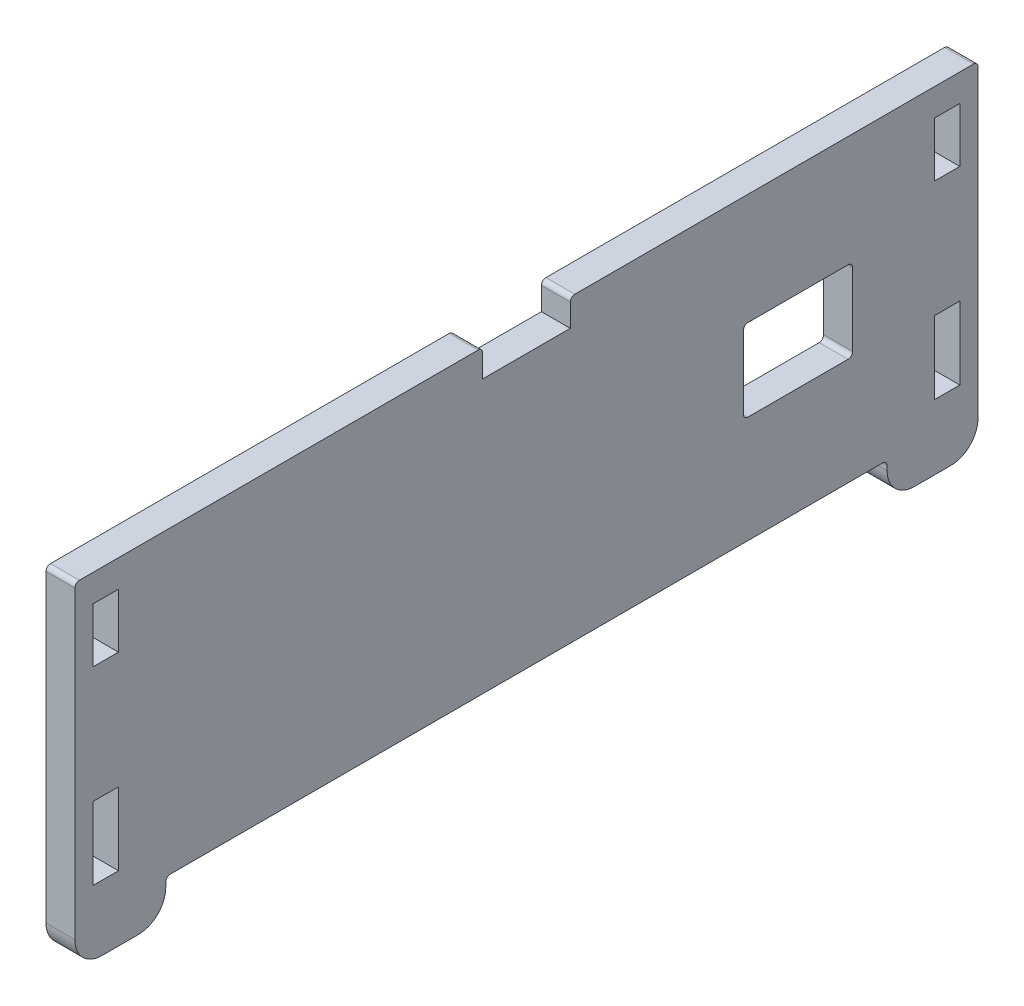
SolidWorks part; units mm, degrees
ref_plane "Front Plane" through (0, 0, 0) normal (0, 0, 1) x (1, 0, 0)
ref_plane "Top Plane" through (0, 0, 0) normal (0, 1, 0) x (1, 0, 0)
ref_plane "Right Plane" through (0, 0, 0) normal (1, 0, 0) x (0, 0, -1)
sketch "Sketch1" plane through (0, 0, 0) normal (1, 0, 0) x (0, 0, -1)
  line L1 (-49.675, -18.5) -> (49.675, -18.5)
  line L2 (-49.675, -18.5) -> (-49.675, 18.5)
  line L3 (-49.675, 18.5) -> (49.675, 18.5)
  line L4 (49.675, -18.5) -> (49.675, 18.5)
  line L5 (-49.675, -18.5) -> (49.675, 18.5) construction
  line L6 (-49.675, 18.5) -> (49.675, -18.5) construction
  point P0 (0, 0)
  dimension "D1" = 99.35
  dimension "D2" = 37
extrude "Boss-Extrude1" add sketch "Sketch1" along normal blind 3.175
sketch "Sketch2" plane through (3.175, 0, 0) normal (1, 0, 0) x (0, 0, -1)
  line L0 (49.675, 18.5) -> (-49.675, 18.5) construction
  line L1 (-47.675, 15.5) -> (-44.875, 15.5)
  line L2 (-47.675, 15.5) -> (-47.675, 9.5)
  line L3 (-47.675, 9.5) -> (-44.875, 9.5)
  line L4 (-44.875, 15.5) -> (-44.875, 9.5)
  line L5 (-49.675, 18.5) -> (-49.675, -18.5) construction
  line L6 (49.675, -18.5) -> (49.675, 18.5) construction
  line L7 (44.875, 15.5) -> (47.675, 15.5)
  line L8 (44.875, 15.5) -> (44.875, 9.5)
  line L9 (44.875, 9.5) -> (47.675, 9.5)
  line L10 (47.675, 15.5) -> (47.675, 9.5)
  line L11 (-49.675, -18.5) -> (49.675, -18.5) construction
  line L12 (-47.675, -3.325) -> (-44.875, -3.325)
  line L13 (-47.675, -3.325) -> (-47.675, -11.325)
  line L14 (-47.675, -11.325) -> (-44.875, -11.325)
  line L15 (-44.875, -3.325) -> (-44.875, -11.325)
  line L17 (44.875, -3.325) -> (47.675, -3.325)
  line L18 (44.875, -3.325) -> (44.875, -11.325)
  line L19 (44.875, -11.325) -> (47.675, -11.325)
  line L20 (47.675, -3.325) -> (47.675, -11.325)
  dimension "D1" = 2.8
  dimension "D2" = 6
  dimension "D3" = 3
  dimension "D4" = 2
  dimension "D5" = 2.8
  dimension "D6" = 3
  dimension "D7" = 2
  dimension "D8" = 6
  dimension "D9" = 2.8
  dimension "D10" = 8
  dimension "D11" = 2
  dimension "D12" = 7.175
  dimension "D13" = 8
  dimension "D14" = 2.8
  dimension "D15" = 2
  dimension "D16" = 7.175
extrude "Cut-Extrude1" cut sketch "Sketch2" against normal through all
sketch "Sketch3" plane through (3.175, 0, 0) normal (1, 0, 0) x (0, 0, -1)
  line L0 (-49.675, -18.5) -> (49.675, -18.5) construction
  line L1 (-39.675, -18.5) -> (39.675, -18.5)
  line L2 (-39.675, -18.5) -> (-39.675, -14.5)
  line L3 (-39.675, -14.5) -> (39.675, -14.5)
  line L4 (39.675, -18.5) -> (39.675, -14.5)
  line L5 (49.675, 18.5) -> (-49.675, 18.5) construction
  line L6 (-49.675, 18.5) -> (-49.675, -18.5) construction
  line L7 (49.675, -18.5) -> (49.675, 18.5) construction
  dimension "D1" = 33
  dimension "D2" = 10
  dimension "D3" = 10
extrude "Cut-Extrude2" cut sketch "Sketch3" against normal through all
fillet "Fillet1" radius 3 4 edges at (1.5875, -18.5, -49.675) (1.5875, -18.5, -39.675) (1.5875, -18.5, 39.675) (1.5875, -18.5, 49.675)
fillet "Fillet2" radius 0.5 4 edges at (1.5875, 18.5, -49.675) (1.5875, 18.5, 49.675) (1.5875, -14.5, -39.675) (1.5875, -14.5, 39.675)
sketch "Sketch4" plane through (3.175, 0, 0) normal (1, 0, 0) x (0, 0, -1)
  line L0 (49.175, 18.5) -> (-49.175, 18.5) construction
  line L1 (-4.825, 18.5) -> (4.825, 18.5)
  line L2 (-4.825, 18.5) -> (-4.825, 15.5)
  line L3 (-4.825, 15.5) -> (4.825, 15.5)
  line L4 (4.825, 18.5) -> (4.825, 15.5)
  dimension "D1" = 9.65
  dimension "D2" = 4.825
  dimension "D3" = 3
extrude "Cut-Extrude3" cut sketch "Sketch4" against normal through all
sketch "Sketch5" plane through (3.175, 0, 0) normal (1, 0, 0) x (0, 0, -1)
  line L0 (44.875, -3.325) -> (44.875, -11.325) construction
  line L1 (23.875, 6.275) -> (35.875, 6.275)
  line L2 (23.875, 6.275) -> (23.875, -2.725)
  line L3 (23.875, -2.725) -> (35.875, -2.725)
  line L4 (35.875, 6.275) -> (35.875, -2.725)
  line L6 (39.175, -14.5) -> (-39.175, -14.5) construction
  dimension "D1" = 9
  dimension "D2" = 11.775
  dimension "D3" = 12
  dimension "D4" = 9
extrude "Cut-Extrude4" cut sketch "Sketch5" against normal through all
fillet "Fillet3" radius 0.5 4 edges at (1.5875, -2.725, -23.875) (1.5875, -2.725, -35.875) (1.5875, 6.275, -35.875) (1.5875, 6.275, -23.875)
fillet "Fillet4" radius 0.5 2 edges at (1.5875, 18.5, -4.825) (1.5875, 18.5, 4.825)
